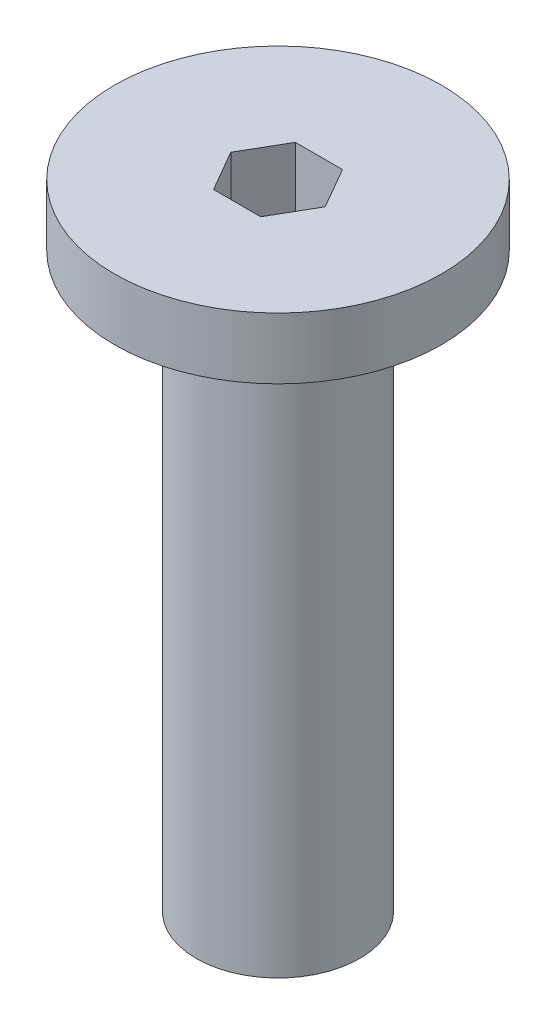
SolidWorks part; units mm, degrees
material "AISI 304"
ref_plane "Front Plane" through (0, 0, 0) normal (0, 0, 1) x (1, 0, 0)
ref_plane "Top Plane" through (0, 0, 0) normal (0, 1, 0) x (1, 0, 0)
ref_plane "Right Plane" through (0, 0, 0) normal (1, 0, 0) x (0, 0, -1)
sketch "Sketch1" plane through (0, 0, 0) normal (0, 0, 1) x (1, 0, 0)
  line L0 (0, 61.6916) -> (0, -59.3578) construction
  line L1 (0, -14) -> (2, -14)
  line L2 (2, -14) -> (2, 0)
  line L3 (2, 0) -> (4, 0)
  line L4 (4, 0) -> (4, 1.5)
  line L5 (4, 1.5) -> (0, 1.5)
  line L6 (0, 1.5) -> (0, -14)
  dimension "L" = 14
  dimension "A" = 8
  dimension "M" = 4
  dimension "H" = 1.5
revolve "Revolve1" add sketch "Sketch1" angle 360 about L0
cosmetic thread "Cosmetic Thread1"
sketch "Sketch2" plane through (0, 1.5, 0) normal (0, 1, 0) x (-1, 0, 0)
  line L1 (-0.5774, -1) -> (0.5774, -1)
  line L2 (0.5774, -1) -> (1.1547, 0)
  line L3 (1.1547, 0) -> (0.5774, 1)
  line L4 (0.5774, 1) -> (-0.5774, 1)
  line L5 (-0.5774, 1) -> (-1.1547, 0)
  line L6 (-1.1547, 0) -> (-0.5774, -1)
  circle A0 centre (0, 0) radius 1 construction
  dimension "B" = 2
extrude "Cut-Extrude1" cut sketch "Sketch2" against normal blind 2.5
